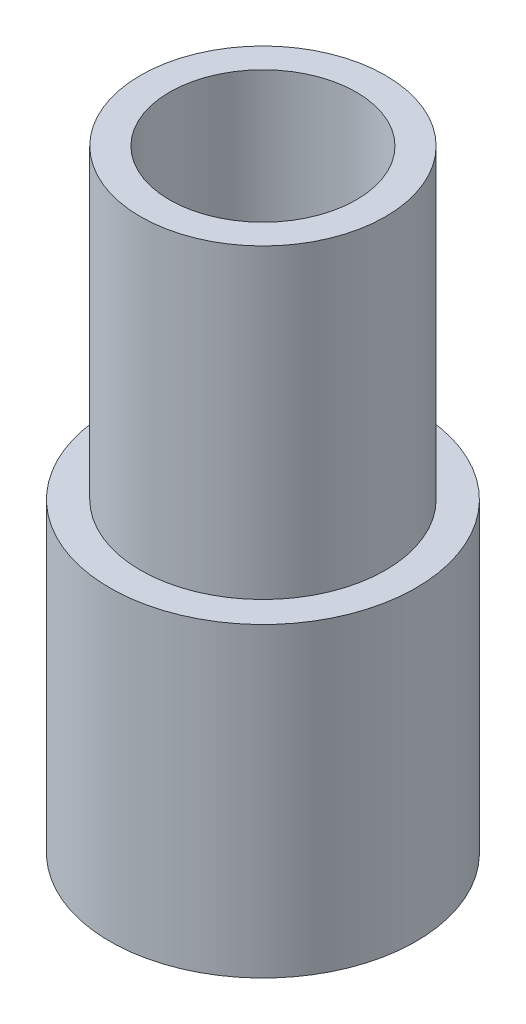
SolidWorks part; units mm, degrees
ref_plane "Front Plane" through (0, 0, 0) normal (0, 0, 1) x (1, 0, 0)
ref_plane "Top Plane" through (0, 0, 0) normal (0, 1, 0) x (1, 0, 0)
ref_plane "Right Plane" through (0, 0, 0) normal (1, 0, 0) x (0, 0, -1)
sketch "Sketch2" plane through (0, 0, 0) normal (0, 1, 0) x (1, 0, 0)
  circle A0 centre (0, 0) radius 4
  dimension "D1" = 8
extrude "Boss-Extrude1" add sketch "Sketch2" along normal blind 10
sketch "Sketch3" plane through (0, 10, 0) normal (0, 1, 0) x (1, 0, 0)
  circle A0 centre (0, 0) radius 3.05
  dimension "D1" = 6.1
extrude "Cut-Extrude3" cut sketch "Sketch3" against normal blind 8
sketch "Sketch4" plane through (0, 0, 0) normal (0, -1, 0) x (1, 0, 0)
  circle A0 centre (0, 0) radius 5
  dimension "D1" = 10
extrude "Boss-Extrude3" add sketch "Sketch4" along normal blind 10
sketch "Sketch5" plane through (0, -10, 0) normal (0, -1, 0) x (1, 0, 0)
  circle A0 centre (0, 0) radius 4.05
extrude "Cut-Extrude4" cut sketch "Sketch5" against normal blind 8
